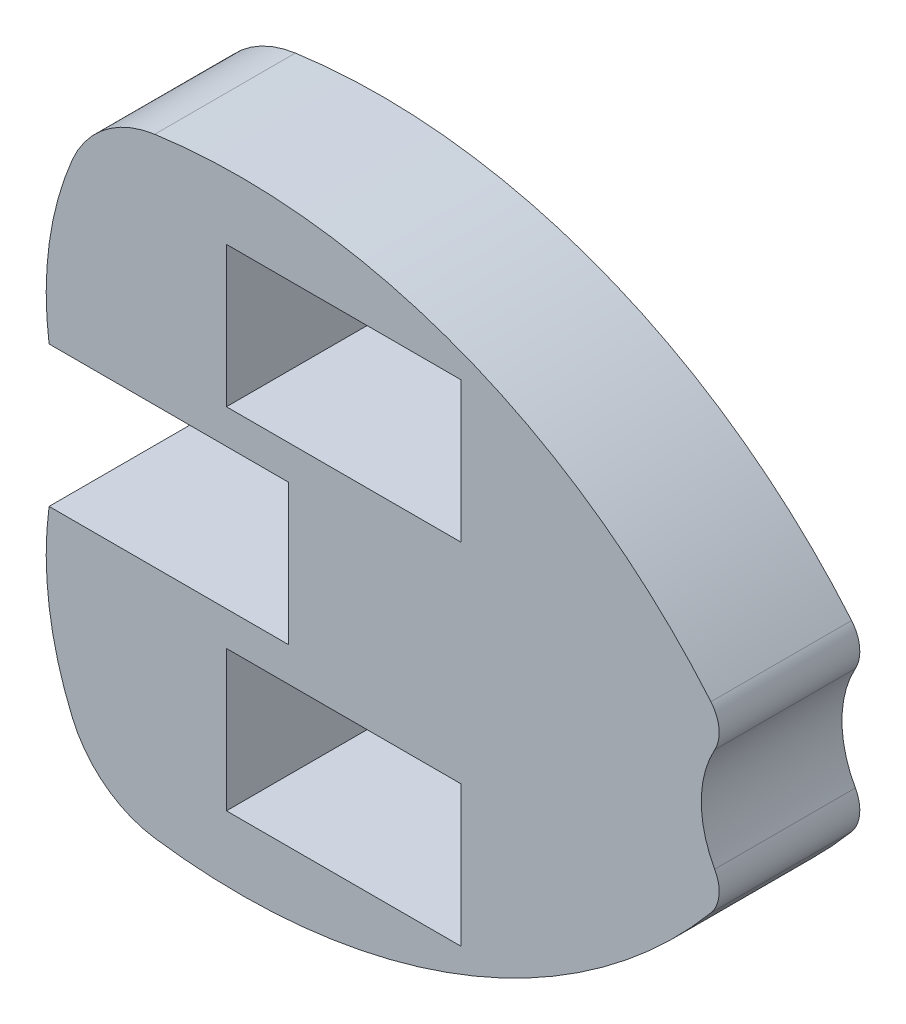
SolidWorks part; units mm, degrees
ref_plane "Front Plane" through (0, 0, 0) normal (0, 0, 1) x (1, 0, 0)
ref_plane "Top Plane" through (0, 0, 0) normal (0, 1, 0) x (1, 0, 0)
ref_plane "Right Plane" through (0, 0, 0) normal (1, 0, 0) x (0, 0, -1)
sketch "Sketch1" plane through (0, 0, 0) normal (0, 0, 1) x (1, 0, 0)
  line L0 (109.9759, -1.524) -> (107.3837, -1.524)
  line L1 (111.8457, 1.8958) -> (111.8457, 0.3718)
  line L2 (109.3057, -3.4198) -> (111.8457, -3.4198)
  line L3 (109.3057, -1.8958) -> (111.8457, -1.8958)
  line L4 (109.3057, -3.4198) -> (109.3057, -1.8958)
  line L5 (111.8457, -3.4198) -> (111.8457, -1.8958)
  line L6 (109.9759, -1.524) -> (109.9759, 0)
  line L7 (109.9759, -0.762) -> (105.7894, -0.762) construction
  line L8 (109.3057, 1.8958) -> (109.3057, 0.3718)
  line L9 (109.3057, 0.3718) -> (111.8457, 0.3718)
  line L10 (109.3057, 1.8958) -> (111.8457, 1.8958)
  line L11 (107.3837, 0) -> (109.9759, 0)
  arc A0 (107.3837, -1.524) -> (107.6364, -3.3808) centre (110.8921, -1.992) ccw
  arc A1 (114.5548, -1.7528) -> (108.5285, -4.0642) centre (109.4562, 2.5287) cw
  arc A2 (114.5548, 0.2288) -> (108.5285, 2.5402) centre (109.4562, -4.0527) ccw
  arc A3 (107.3837, 0) -> (107.6364, 1.8568) centre (110.8921, 0.468) cw
  arc A4 (114.5959, -0.2016) -> (114.5959, -1.3224) centre (115.6022, -0.762) ccw
  arc A5 (114.5548, -1.7528) -> (114.5959, -1.3224) centre (114.263, -1.5078) ccw
  arc A6 (114.5548, 0.2288) -> (114.5959, -0.2016) centre (114.263, -0.0162) cw
  arc A7 (108.5285, -4.0642) -> (107.6364, -3.3808) centre (108.6878, -2.9323) cw
  arc A8 (108.5285, 2.5402) -> (107.6364, 1.8568) centre (108.6878, 1.4083) ccw
  point P28 (114.7384, -1.524)
  point P31 (114.7384, 0)
  point P34 (107.9474, -3.9559)
  point P37 (107.9474, 2.4319)
  dimension "D1" = 0.381
  dimension "D2" = 1.143
extrude "Boss-Extrude1" add sketch "Sketch1" along normal blind 1.524
